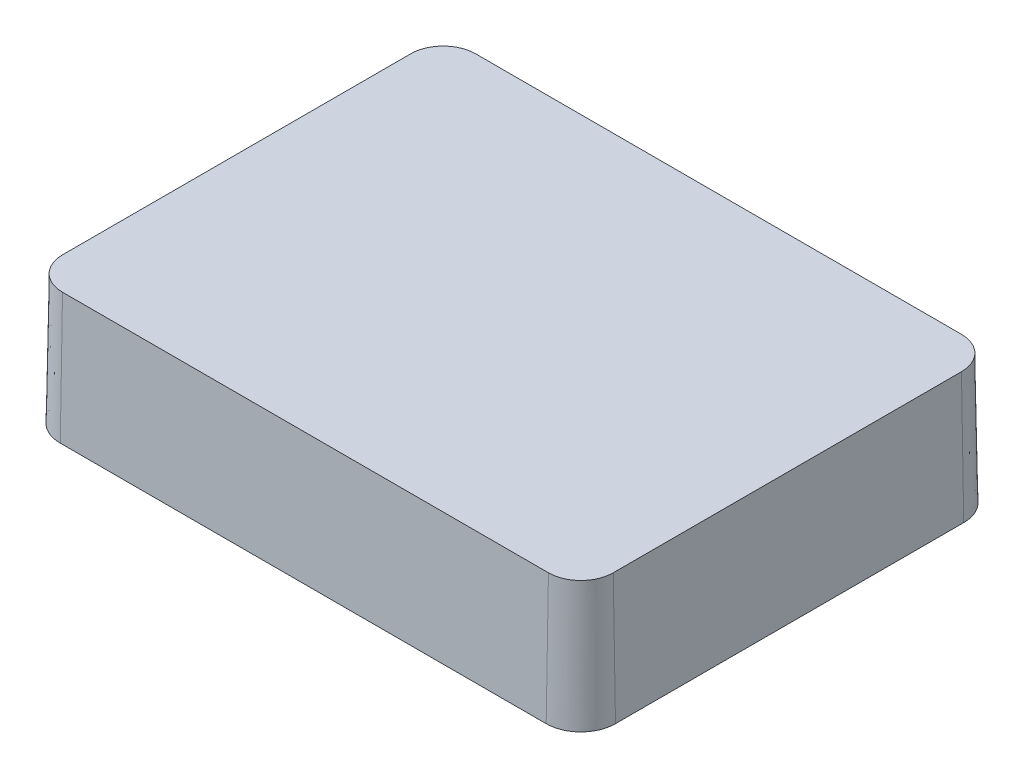
SolidWorks part; units mm, degrees
ref_plane "Front Plane" through (0, 0, 0) normal (0, 0, 1) x (1, 0, 0)
ref_plane "Top Plane" through (0, 0, 0) normal (0, 1, 0) x (1, 0, 0)
ref_plane "Right Plane" through (0, 0, 0) normal (1, 0, 0) x (0, 0, -1)
sketch "Sketch1" plane through (0, 0, 0) normal (0, 1, 0) x (1, 0, 0)
  line L1 (-7.5, -6.375) -> (7.5, -6.375)
  line L2 (-8.5, -5.375) -> (-8.5, 5.375)
  line L3 (-7.5, 6.375) -> (7.5, 6.375)
  line L4 (8.5, -5.375) -> (8.5, 5.375)
  line L5 (-8.5, -6.375) -> (8.5, 6.375) construction
  line L6 (-8.5, 6.375) -> (8.5, -6.375) construction
  arc A0 (-8.5, 5.375) -> (-7.5, 6.375) centre (-7.5, 5.375) cw
  arc A1 (8.5, 5.375) -> (7.5, 6.375) centre (7.5, 5.375) ccw
  arc A2 (8.5, -5.375) -> (7.5, -6.375) centre (7.5, -5.375) cw
  arc A3 (-7.5, -6.375) -> (-8.5, -5.375) centre (-7.5, -5.375) cw
  point P0 (0, 0)
  dimension "D3" = 1
  dimension "D1" = 17
  dimension "D2" = 12.75
extrude "Boss-Extrude1" add sketch "Sketch1" against normal blind 4 draft 1 draft outward yes
shell "Shell1" thickness 0.5
sketch "Sketch2" plane through (0, -0.5, 0) normal (0, -1, 0) x (1, 0, 0)
  line L0 (-0.6, 2.9308) -> (-0.6, 0.6)
  line L1 (-2.9308, 0.6) -> (-0.6, 0.6)
  line L2 (0, -2.2) -> (0, 2.2) construction
  line L3 (2.2, 0) -> (-2.2, 0) construction
  line L4 (-2.9308, -0.6) -> (-0.6, -0.6)
  line L5 (0.6, 2.9308) -> (0.6, 0.6)
  line L6 (-0.6, -0.6) -> (-0.6, -2.9308)
  line L7 (0.6, -0.6) -> (0.6, -2.9308)
  line L8 (0.6, -0.6) -> (2.9308, -0.6)
  line L9 (0.6, 0.6) -> (2.9308, 0.6)
  arc A0 (-2.9308, -0.6) -> (-0.6, -2.9308) centre (0, 0) ccw
  arc A1 (2.9308, 0.6) -> (0.6, 2.9308) centre (0, 0) ccw
  arc A2 (-0.6, 2.9308) -> (-2.9308, 0.6) centre (0, 0) ccw
  arc A3 (0.6, -2.9308) -> (2.9308, -0.6) centre (0, 0) ccw
  dimension "D1" = 0.6
  dimension "D2" = 0.6
extrude "Boss-Extrude2" add sketch "Sketch2" along normal blind 5.5 draft 1.5
